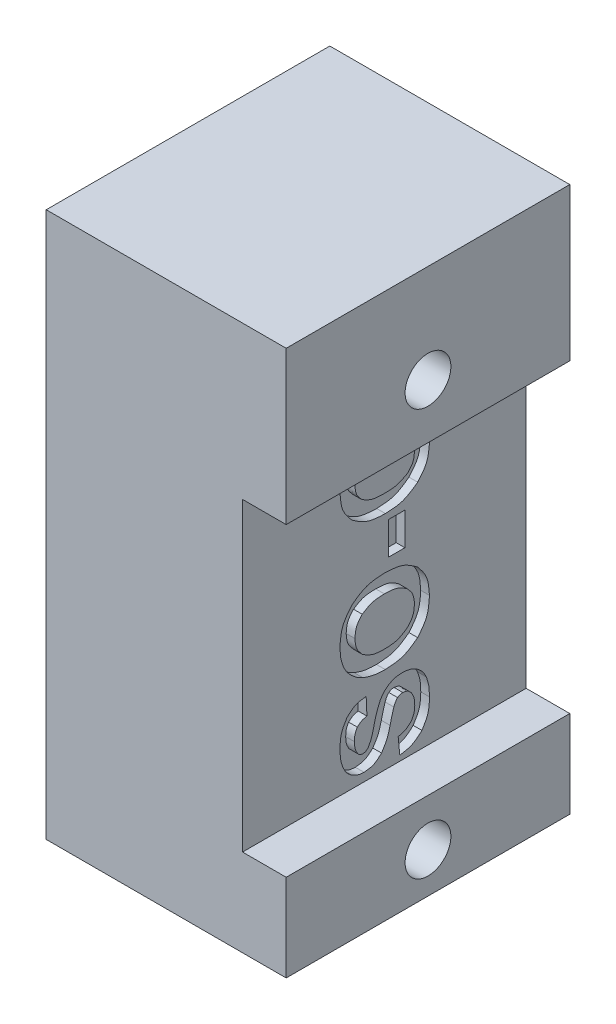
SolidWorks part; units mm, degrees
ref_plane "Front Plane" through (0, 0, 0) normal (0, 0, 1) x (1, 0, 0)
ref_plane "Top Plane" through (0, 0, 0) normal (0, 1, 0) x (1, 0, 0)
ref_plane "Right Plane" through (0, 0, 0) normal (1, 0, 0) x (0, 0, -1)
ref_plane "Plan1" through (-30.7, 0, 0) normal (-1, 0, 0) x (0, -1, 0)
sketch "Esquisse1" plane through (-30.7, 0, 0) normal (-1, 0, 0) x (0, -1, 0)
  line L0 (12.5, 6.5) -> (-12.5, 6.5)
  line L1 (-12.5, 6.5) -> (-12.5, -6.5)
  line L2 (-12.5, -6.5) -> (12.5, -6.5)
  line L3 (12.5, -6.5) -> (12.5, 6.5)
extrude "Boss.-Extru.1" add sketch "Esquisse1" against normal blind 11
sketch "Esquisse2" plane through (0, 0, 6.5) normal (0, 0, 1) x (1, 0, 0)
  line L0 (-19.7, 5.5) -> (-21.7, 5.5)
  line L1 (-21.7, 5.5) -> (-21.7, -8.5)
  line L2 (-21.7, -8.5) -> (-19.7, -8.5)
  line L3 (-19.7, -8.5) -> (-19.7, 5.5)
extrude "Enlèv. mat.-Extru.1" cut sketch "Esquisse2" against normal through all
ref_plane "Plan2" through (-22.9, 0, 0) normal (1, 0, 0) x (0, 0, -1)
sketch "Esquisse3" plane through (-22.9, 0, 0) normal (1, 0, 0) x (0, 0, -1)
  spline S0 degree 3 poles (0.0406, -4.523) (-0.0464, -4.5207) (-0.2198, -4.5161) (-0.479, -4.4914) (-0.7313, -4.4272) (-0.8949, -4.3703) (-0.977, -4.3417) knots 0 0 0 0 0.251163 0.500347 0.749185 1 1 1 1
  spline S1 degree 3 poles (-0.977, -4.3417) (-1.0264, -4.317) (-1.1248, -4.2677) (-1.2674, -4.1841) (-1.3977, -4.0823) (-1.4798, -4.009) (-1.521, -3.9723) knots 0 0 0 0 0.250726 0.49999 0.749263 1 1 1 1
  spline S2 degree 3 poles (-1.521, -3.9723) (-1.5572, -3.9341) (-1.6293, -3.8581) (-1.7291, -3.7363) (-1.8091, -3.6008) (-1.8551, -3.5066) (-1.8782, -3.4594) knots 0 0 0 0 0.251028 0.500121 0.749093 1 1 1 1
  spline S3 degree 3 poles (-1.8782, -3.4594) (-1.9022, -3.3903) (-1.9501, -3.2527) (-2.0051, -3.0408) (-2.0277, -2.823) (-2.0327, -2.6773) (-2.0352, -2.6042) knots 0 0 0 0 0.250839 0.499795 0.748957 1 1 1 1
  spline S4 degree 3 poles (-2.0352, -2.6042) (-2.0263, -2.4738) (-2.0089, -2.2171) (-1.9297, -1.8371) (-1.7354, -1.5011) (-1.5734, -1.3021) (-1.4912, -1.2009) knots 0 0 0 0 0.254339 0.500753 0.746403 1 1 1 1
  spline S5 degree 3 poles (-1.4912, -1.2009) (-1.3801, -1.119) (-1.1609, -0.9574) (-0.7951, -0.7683) (-0.3898, -0.6956) (-0.1168, -0.6817) (0.0217, -0.6746) knots 0 0 0 0 0.253014 0.498879 0.745877 1 1 1 1
  spline S6 degree 3 poles (0.0217, -0.6746) (0.1592, -0.6817) (0.4304, -0.6956) (0.833, -0.7679) (1.1966, -0.9554) (1.4145, -1.1156) (1.525, -1.1969) knots 0 0 0 0 0.254089 0.501098 0.746997 1 1 1 1
  spline S7 degree 3 poles (1.525, -1.1969) (1.6071, -1.2974) (1.7687, -1.4953) (1.9627, -1.8296) (2.0416, -2.2079) (2.0589, -2.4635) (2.0677, -2.5934) knots 0 0 0 0 0.253616 0.499231 0.745626 1 1 1 1
  spline S8 degree 3 poles (2.0677, -2.5934) (2.0591, -2.724) (2.0424, -2.9812) (1.9645, -3.362) (1.7713, -3.6993) (1.6098, -3.8992) (1.5277, -4.0007) knots 0 0 0 0 0.254373 0.500837 0.746452 1 1 1 1
  spline S9 degree 3 poles (1.5277, -4.0007) (1.4186, -4.0816) (1.2034, -4.2413) (0.8441, -4.4287) (0.4454, -4.5014) (0.1768, -4.5157) (0.0406, -4.523) knots 0 0 0 0 0.253057 0.498943 0.745899 1 1 1 1
extrude "Enlèv. mat.-Extru.2" cut sketch "Esquisse3" against normal blind 0.4 from surface at 1.2 starting at face at (-21.7, -1.5, 0)
ref_plane "Plan3" through (-20.9, 0, 0) normal (-1, 0, 0) x (0, -1, 0)
sketch "Esquisse4" plane through (-20.9, 0, 0) normal (-1, 0, 0) x (0, -1, 0)
  spline S0 degree 3 poles (3.3945, 1.0108) (3.4439, 0.9338) (3.5416, 0.7816) (3.6512, 0.531) (3.6895, 0.2603) (3.6949, 0.0785) (3.6976, -0.0135) knots 0 0 0 0 0.25227 0.498455 0.74619 1 1 1 1
  spline S1 degree 3 poles (3.6976, -0.0135) (3.6944, -0.1055) (3.6882, -0.2873) (3.6479, -0.5578) (3.5357, -0.8072) (3.4365, -0.9586) (3.3863, -1.0352) knots 0 0 0 0 0.253803 0.501421 0.747611 1 1 1 1
  spline S2 degree 3 poles (3.3863, -1.0352) (3.3308, -1.0859) (3.2217, -1.1856) (3.0352, -1.3087) (2.8182, -1.3627) (2.671, -1.3761) (2.5961, -1.383) knots 0 0 0 0 0.254357 0.499849 0.745494 1 1 1 1
  spline S3 degree 3 poles (2.5961, -1.383) (2.5215, -1.3763) (2.375, -1.3631) (2.1592, -1.3099) (1.9735, -1.1875) (1.8651, -1.0884) (1.8099, -1.0379) knots 0 0 0 0 0.254564 0.500212 0.745644 1 1 1 1
  spline S4 degree 3 poles (1.8099, -1.0379) (1.7599, -0.96) (1.661, -0.8062) (1.5501, -0.5531) (1.5111, -0.2794) (1.5055, -0.0957) (1.5027, -0.0027) knots 0 0 0 0 0.252281 0.498482 0.746207 1 1 1 1
  spline S5 degree 3 poles (1.5027, -0.0027) (1.5053, 0.0886) (1.5105, 0.2691) (1.5481, 0.538) (1.6562, 0.787) (1.7528, 0.9383) (1.8018, 1.0149) knots 0 0 0 0 0.253806 0.501568 0.747758 1 1 1 1
  spline S6 degree 3 poles (1.8018, 1.0149) (1.8578, 1.0649) (1.9678, 1.1631) (2.1562, 1.2828) (2.3738, 1.3329) (2.5211, 1.3446) (2.5961, 1.3505) knots 0 0 0 0 0.254161 0.499437 0.745285 1 1 1 1
  spline S7 degree 3 poles (2.5961, 1.3505) (2.6715, 1.3444) (2.8197, 1.3324) (3.0384, 1.2813) (3.2276, 1.1602) (3.3382, 1.0612) (3.3945, 1.0108) knots 0 0 0 0 0.254675 0.500489 0.745806 1 1 1 1
extrude "Boss.-Extru.2" add sketch "Esquisse4" against normal blind 0.4 from surface at 1.2 starting at face at (-22.1, -2.8567, 0.272)
sketch "Esquisse5" plane through (-22.9, 0, 0) normal (1, 0, 0) x (0, 0, -1)
  line L0 (0.7091, -8.2632) -> (0.6333, -7.4838)
  line L1 (-0.8336, -5.1509) -> (-0.7984, -5.952)
  arc A0 (0.4357, -6.2091) -> (0.2625, -6.8505) centre (10.0642, -9.1532) ccw
  arc A1 (-0.4763, -6.4986) -> (-0.1908, -5.634) centre (3.3483, -7.2821) cw
  spline S0 degree 3 poles (0.6333, -7.4838) (0.6873, -7.4721) (0.794, -7.449) (0.9499, -7.3971) (1.0873, -7.307) (1.1686, -7.2348) (1.2097, -7.1982) knots 0 0 0 0 0.253315 0.501159 0.747839 1 1 1 1
  spline S1 degree 3 poles (1.2097, -7.1982) (1.2385, -7.1546) (1.2952, -7.0685) (1.3611, -6.9272) (1.3864, -6.7735) (1.3913, -6.6701) (1.3938, -6.6177) knots 0 0 0 0 0.252518 0.499046 0.746536 1 1 1 1
  spline S2 degree 3 poles (1.3938, -6.6177) (1.3923, -6.5657) (1.3894, -6.4628) (1.3688, -6.3095) (1.3097, -6.1665) (1.2568, -6.0788) (1.23, -6.0345) knots 0 0 0 0 0.253455 0.501409 0.747951 1 1 1 1
  spline S3 degree 3 poles (1.23, -6.0345) (1.2039, -6.0074) (1.1526, -5.9541) (1.064, -5.886) (0.9574, -5.8527) (0.8843, -5.8431) (0.8471, -5.8383) knots 0 0 0 0 0.255257 0.500969 0.745695 1 1 1 1
  spline S4 degree 3 poles (0.8471, -5.8383) (0.8254, -5.8398) (0.7825, -5.8427) (0.7189, -5.8551) (0.661, -5.8843) (0.6255, -5.9086) (0.6076, -5.9208) knots 0 0 0 0 0.253127 0.500331 0.7472 1 1 1 1
  spline S5 degree 3 poles (0.6076, -5.9208) (0.5885, -5.9418) (0.5505, -5.9834) (0.501, -6.0524) (0.4653, -6.1294) (0.4456, -6.1824) (0.4357, -6.2091) knots 0 0 0 0 0.251044 0.499054 0.748003 1 1 1 1
  spline S6 degree 3 poles (0.2625, -6.8505) (0.242, -6.9312) (0.2011, -7.0918) (0.1235, -7.3279) (0.0084, -7.5484) (-0.0836, -7.6855) (-0.1299, -7.7544) knots 0 0 0 0 0.251646 0.500889 0.749255 1 1 1 1
  spline S7 degree 3 poles (-0.1299, -7.7544) (-0.1858, -7.8067) (-0.2956, -7.9094) (-0.4832, -8.0377) (-0.7028, -8.0964) (-0.8522, -8.1119) (-0.9283, -8.1198) knots 0 0 0 0 0.254538 0.500238 0.745696 1 1 1 1
  spline S8 degree 3 poles (-0.9283, -8.1198) (-0.9785, -8.116) (-1.0782, -8.1086) (-1.2261, -8.0813) (-1.3643, -8.0217) (-1.4514, -7.9726) (-1.4953, -7.9479) knots 0 0 0 0 0.251968 0.499906 0.747939 1 1 1 1
  spline S9 degree 3 poles (-1.4953, -7.9479) (-1.538, -7.9145) (-1.6229, -7.8484) (-1.7384, -7.7347) (-1.8252, -7.5978) (-1.873, -7.5013) (-1.8972, -7.4526) knots 0 0 0 0 0.251958 0.499717 0.747761 1 1 1 1
  spline S10 degree 3 poles (-1.8972, -7.4526) (-1.9187, -7.3896) (-1.9617, -7.2639) (-2.0103, -7.0702) (-2.0295, -6.8715) (-2.0333, -6.7386) (-2.0352, -6.6719) knots 0 0 0 0 0.250796 0.49971 0.748914 1 1 1 1
  spline S11 degree 3 poles (-2.0352, -6.6719) (-2.0322, -6.5711) (-2.0262, -6.372) (-1.9846, -6.0754) (-1.8664, -5.8001) (-1.761, -5.6323) (-1.7077, -5.5474) knots 0 0 0 0 0.253652 0.501459 0.747802 1 1 1 1
  spline S12 degree 3 poles (-1.7077, -5.5474) (-1.6465, -5.4908) (-1.526, -5.3796) (-1.3196, -5.242) (-1.0797, -5.1788) (-0.9165, -5.1603) (-0.8336, -5.1509) knots 0 0 0 0 0.253962 0.499506 0.745552 1 1 1 1
  spline S13 degree 3 poles (-0.7984, -5.952) (-0.8399, -5.9605) (-0.922, -5.9772) (-1.0418, -6.0164) (-1.1463, -6.0868) (-1.2073, -6.1437) (-1.2382, -6.1725) knots 0 0 0 0 0.253848 0.501425 0.747569 1 1 1 1
  spline S14 degree 3 poles (-1.2382, -6.1725) (-1.2603, -6.2114) (-1.304, -6.2885) (-1.3523, -6.4133) (-1.3689, -6.546) (-1.3711, -6.635) (-1.3721, -6.68) knots 0 0 0 0 0.251822 0.498619 0.746797 1 1 1 1
  spline S15 degree 3 poles (-1.3721, -6.68) (-1.3706, -6.7282) (-1.3675, -6.8238) (-1.3488, -6.9664) (-1.2974, -7.1007) (-1.2517, -7.1844) (-1.2287, -7.2267) knots 0 0 0 0 0.252764 0.500989 0.748223 1 1 1 1
  spline S16 degree 3 poles (-1.2287, -7.2267) (-1.2124, -7.2449) (-1.1806, -7.2807) (-1.1239, -7.3258) (-1.0543, -7.346) (-1.0067, -7.3512) (-0.9824, -7.3539) knots 0 0 0 0 0.255761 0.500136 0.744372 1 1 1 1
  spline S17 degree 3 poles (-0.9824, -7.3539) (-0.9591, -7.3511) (-0.9134, -7.3457) (-0.8465, -7.3259) (-0.7905, -7.2843) (-0.7581, -7.2515) (-0.7415, -7.2348) knots 0 0 0 0 0.254456 0.499368 0.744924 1 1 1 1
  spline S18 degree 3 poles (-0.7415, -7.2348) (-0.7101, -7.1772) (-0.6474, -7.0624) (-0.5718, -6.8807) (-0.5192, -6.6911) (-0.4906, -6.5629) (-0.4763, -6.4986) knots 0 0 0 0 0.250288 0.499061 0.748735 1 1 1 1
  spline S19 degree 3 poles (-0.1908, -5.634) (-0.1647, -5.5907) (-0.1129, -5.5048) (-0.0228, -5.3838) (0.0901, -5.2837) (0.1715, -5.225) (0.2124, -5.1955) knots 0 0 0 0 0.251753 0.500105 0.748351 1 1 1 1
  spline S20 degree 3 poles (0.2124, -5.1955) (0.262, -5.1711) (0.3603, -5.1225) (0.5157, -5.0664) (0.6793, -5.0441) (0.7891, -5.0395) (0.8444, -5.0372) knots 0 0 0 0 0.251571 0.49951 0.747941 1 1 1 1
  spline S21 degree 3 poles (0.8444, -5.0372) (0.9008, -5.0413) (1.0129, -5.0494) (1.1792, -5.0795) (1.335, -5.1452) (1.4335, -5.1994) (1.4831, -5.2267) knots 0 0 0 0 0.2519 0.499919 0.74802 1 1 1 1
  spline S22 degree 3 poles (1.4831, -5.2267) (1.5303, -5.2624) (1.6239, -5.3332) (1.7516, -5.4554) (1.8471, -5.6042) (1.8993, -5.7094) (1.9256, -5.7625) knots 0 0 0 0 0.252157 0.499829 0.747674 1 1 1 1
  spline S23 degree 3 poles (1.9256, -5.7625) (1.9485, -5.8324) (1.9943, -5.9717) (2.0455, -6.186) (2.0651, -6.4055) (2.0686, -6.5522) (2.0704, -6.6258) knots 0 0 0 0 0.250726 0.499666 0.74894 1 1 1 1
  spline S24 degree 3 poles (2.0704, -6.6258) (2.0666, -6.7296) (2.0592, -6.9347) (2.0136, -7.2401) (1.8884, -7.5223) (1.7783, -7.6944) (1.7226, -7.7815) knots 0 0 0 0 0.253588 0.501272 0.747677 1 1 1 1
  spline S25 degree 3 poles (1.7226, -7.7815) (1.6509, -7.846) (1.5093, -7.9735) (1.2686, -8.1316) (0.993, -8.2146) (0.8045, -8.2469) (0.7091, -8.2632) knots 0 0 0 0 0.252842 0.499034 0.746202 1 1 1 1
extrude "Enlèv. mat.-Extru.3" cut sketch "Esquisse5" against normal blind 0.4 from surface at 1.2 starting at face at (-21.7, -2.8567, 0.272)
sketch "Esquisse6" plane through (-22.9, 0, 0) normal (1, 0, 0) x (0, 0, -1)
  line L0 (0.5413, 4.3403) -> (0.7876, 5.117)
  line L1 (-0.8742, 5.1062) -> (-0.6847, 4.3133)
  spline S0 degree 3 poles (0.7876, 5.117) (0.8798, 5.0872) (1.0626, 5.0282) (1.3263, 4.9103) (1.5526, 4.7308) (1.6853, 4.5927) (1.7524, 4.523) knots 0 0 0 0 0.252928 0.500799 0.747866 1 1 1 1
  spline S1 degree 3 poles (1.7524, 4.523) (1.8008, 4.4425) (1.8968, 4.2832) (2.0088, 4.026) (2.0536, 3.7491) (2.0629, 3.5629) (2.0677, 3.4689) knots 0 0 0 0 0.252212 0.499368 0.74716 1 1 1 1
  spline S2 degree 3 poles (2.0677, 3.4689) (2.0576, 3.347) (2.0378, 3.1073) (1.9556, 2.7533) (1.764, 2.4446) (1.6074, 2.2624) (1.5277, 2.1698) knots 0 0 0 0 0.254308 0.50034 0.746026 1 1 1 1
  spline S3 degree 3 poles (1.5277, 2.1698) (1.4188, 2.0909) (1.204, 1.9353) (0.8468, 1.7529) (0.4521, 1.6821) (0.1862, 1.6681) (0.0514, 1.661) knots 0 0 0 0 0.252947 0.498981 0.746045 1 1 1 1
  spline S4 degree 3 poles (0.0514, 1.661) (-0.0885, 1.6675) (-0.3646, 1.6802) (-0.7749, 1.7496) (-1.1482, 1.9335) (-1.3732, 2.0921) (-1.4871, 2.1725) knots 0 0 0 0 0.253957 0.501187 0.747218 1 1 1 1
  spline S5 degree 3 poles (-1.4871, 2.1725) (-1.569, 2.2684) (-1.73, 2.4571) (-1.9254, 2.7775) (-2.0069, 3.1438) (-2.0257, 3.3916) (-2.0352, 3.5176) knots 0 0 0 0 0.253896 0.499424 0.745537 1 1 1 1
  spline S6 degree 3 poles (-2.0352, 3.5176) (-2.0282, 3.6261) (-2.0144, 3.8402) (-1.9518, 4.1575) (-1.7985, 4.4423) (-1.67, 4.6135) (-1.6049, 4.7003) knots 0 0 0 0 0.253855 0.500677 0.746814 1 1 1 1
  spline S7 degree 3 poles (-1.6049, 4.7003) (-1.5514, 4.7467) (-1.4452, 4.8388) (-1.2708, 4.9588) (-1.0758, 5.0413) (-0.9417, 5.0845) (-0.8742, 5.1062) knots 0 0 0 0 0.251401 0.499416 0.748016 1 1 1 1
  spline S8 degree 3 poles (-0.6847, 4.3133) (-0.7314, 4.2994) (-0.8239, 4.2719) (-0.9572, 4.2142) (-1.071, 4.1238) (-1.138, 4.0546) (-1.1719, 4.0196) knots 0 0 0 0 0.252921 0.500347 0.747423 1 1 1 1
  spline S9 degree 3 poles (-1.1719, 4.0196) (-1.1986, 3.9787) (-1.2515, 3.8977) (-1.3146, 3.7661) (-1.3412, 3.6226) (-1.3473, 3.5259) (-1.3505, 3.477) knots 0 0 0 0 0.252583 0.499618 0.747039 1 1 1 1
  spline S10 degree 3 poles (-1.3505, 3.477) (-1.3445, 3.4089) (-1.3327, 3.2752) (-1.2842, 3.0782) (-1.1717, 2.9093) (-1.0803, 2.8111) (-1.0338, 2.7612) knots 0 0 0 0 0.254755 0.500309 0.745549 1 1 1 1
  spline S11 degree 3 poles (-1.0338, 2.7612) (-0.9558, 2.7148) (-0.8016, 2.6231) (-0.5493, 2.5235) (-0.28, 2.4911) (-0.0994, 2.488) (-0.0081, 2.4865) knots 0 0 0 0 0.251881 0.498205 0.746319 1 1 1 1
  spline S12 degree 3 poles (-0.0081, 2.4865) (0.0868, 2.4875) (0.2746, 2.4896) (0.5549, 2.5205) (0.8192, 2.6187) (0.9816, 2.7106) (1.0636, 2.7571) knots 0 0 0 0 0.253546 0.501862 0.748327 1 1 1 1
  spline S13 degree 3 poles (1.0636, 2.7571) (1.1103, 2.8059) (1.2018, 2.9016) (1.3152, 3.0671) (1.3646, 3.2615) (1.3768, 3.3935) (1.383, 3.4608) knots 0 0 0 0 0.254637 0.499788 0.745155 1 1 1 1
  spline S14 degree 3 poles (1.383, 3.4608) (1.379, 3.511) (1.3712, 3.6103) (1.34, 3.7571) (1.2685, 3.8892) (1.2097, 3.9695) (1.18, 4.0101) knots 0 0 0 0 0.253298 0.500163 0.746863 1 1 1 1
  spline S15 degree 3 poles (1.18, 4.0101) (1.1339, 4.0503) (1.0425, 4.13) (0.8899, 4.2308) (0.7184, 4.294) (0.6007, 4.3248) (0.5413, 4.3403) knots 0 0 0 0 0.251706 0.498988 0.747283 1 1 1 1
extrude "Enlèv. mat.-Extru.4" cut sketch "Esquisse6" against normal blind 0.4 from surface at 1.2 starting at face at (-21.7, -6.5845, 0.0178)
sketch "Esquisse7" plane through (-21.7, 0, 0) normal (1, 0, 0) x (0, 0, -1)
  line L0 (0.1813, -0.1387) -> (0.9418, -0.1387)
  line L1 (0.9418, -0.1387) -> (0.9418, 1.3552)
  line L2 (0.9418, 1.3552) -> (0.1813, 1.3552)
  line L3 (0.1813, 1.3552) -> (0.1813, -0.1387)
extrude "Enlèv. mat.-Extru.5" cut sketch "Esquisse7" against normal blind 0.4
hole_wizard "Diamètre du perçage Ø2.1 (2.1)1" positions "Esquisse9" profile "Esquisse8" hole size "Ø2.1" standard "Ansi Metric"
sketch "Esquisse9" plane through (-30.7, 0, 0) normal (-1, 0, 0) x (0, 0, 1)
  point P0 (0, 4.5)
sketch "Esquisse8" plane through (-30.7, 4.5, 0) normal (0, 1, 0) x (0, 0, 1)
  line L0 (0, 0) -> (0, 8)
  line L1 (0, 8) -> (1.05, 8)
  line L2 (1.05, 8) -> (1.05, 0)
  line L5 (1.05, 0) -> (0, 0)
  line L10 (0, 8) -> (-1.05, 8) construction
  line L11 (0, -6.35) -> (0, 107.95) construction
  dimension "Diamètre du perçage" = 2.1
  dimension "Profondeur du perçage" = 8
  dimension "Angle de pointe" = 180
hole_wizard "Diamètre du perçage Ø2.1 (2.1)2" positions "Esquisse11" profile "Esquisse10" hole size "Ø2.1" standard "Ansi Metric"
sketch "Esquisse11" plane through (-30.7, 0, 0) normal (-1, 0, 0) x (0, 0, 1)
  point P0 (0, -7)
sketch "Esquisse10" plane through (-30.7, -7, 0) normal (0, 1, 0) x (0, 0, 1)
  line L0 (0, 0) -> (0, 8)
  line L1 (0, 8) -> (1.05, 8)
  line L2 (1.05, 8) -> (1.05, 0)
  line L5 (1.05, 0) -> (0, 0)
  line L10 (0, 8) -> (-1.05, 8) construction
  line L11 (0, -6.35) -> (0, 107.95) construction
  dimension "Diamètre du perçage" = 2.1
  dimension "Profondeur du perçage" = 8
  dimension "Angle de pointe" = 180
hole_wizard "Diamètre du perçage Ø2.1 (2.1)3" positions "Esquisse13" profile "Esquisse12" hole size "Ø2.1" standard "Ansi Metric"
sketch "Esquisse13" plane through (-19.7, 0, 0) normal (1, 0, 0) x (0, 0, -1)
  point P0 (0, 8)
  point P1 (0, -10.65)
sketch "Esquisse12" plane through (-19.7, 8, 0) normal (0, 1, 0) x (0, 0, -1)
  line L0 (0, 0) -> (0, 10)
  line L1 (0, 10) -> (1.05, 10)
  line L2 (1.05, 10) -> (1.05, 0)
  line L5 (1.05, 0) -> (0, 0)
  line L10 (0, 10) -> (-1.05, 10) construction
  line L11 (0, -6.35) -> (0, 107.95) construction
  dimension "Diamètre du perçage" = 2.1
  dimension "Profondeur du perçage" = 10
  dimension "Angle de pointe" = 180
